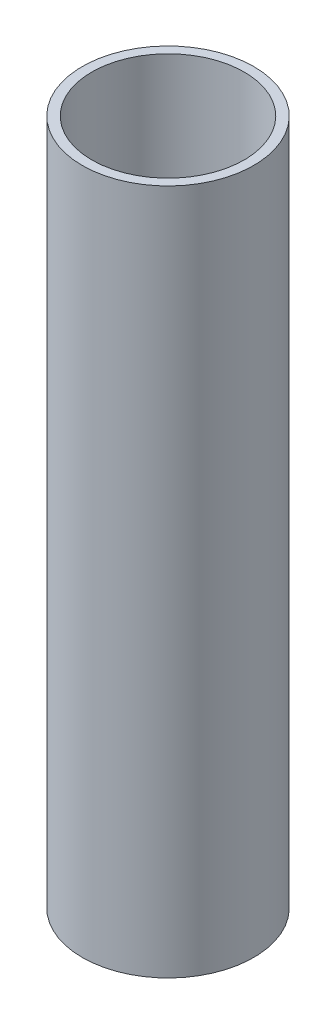
SolidWorks part; units mm, degrees
ref_plane "Front Plane" through (0, 0, 0) normal (0, 0, 1) x (1, 0, 0)
ref_plane "Top Plane" through (0, 0, 0) normal (0, 1, 0) x (1, 0, 0)
ref_plane "Right Plane" through (0, 0, 0) normal (1, 0, 0) x (0, 0, -1)
sketch "Sketch1" plane through (0, 0, 0) normal (0, 1, 0) x (1, 0, 0)
  circle A0 centre (0, 0) radius 50.8
  circle A1 centre (0, 0) radius 57.15
  dimension "D1" = 101.6
  dimension "D2" = 114.3
extrude "Boss-Extrude1" add sketch "Sketch1" along normal blind 457.2
